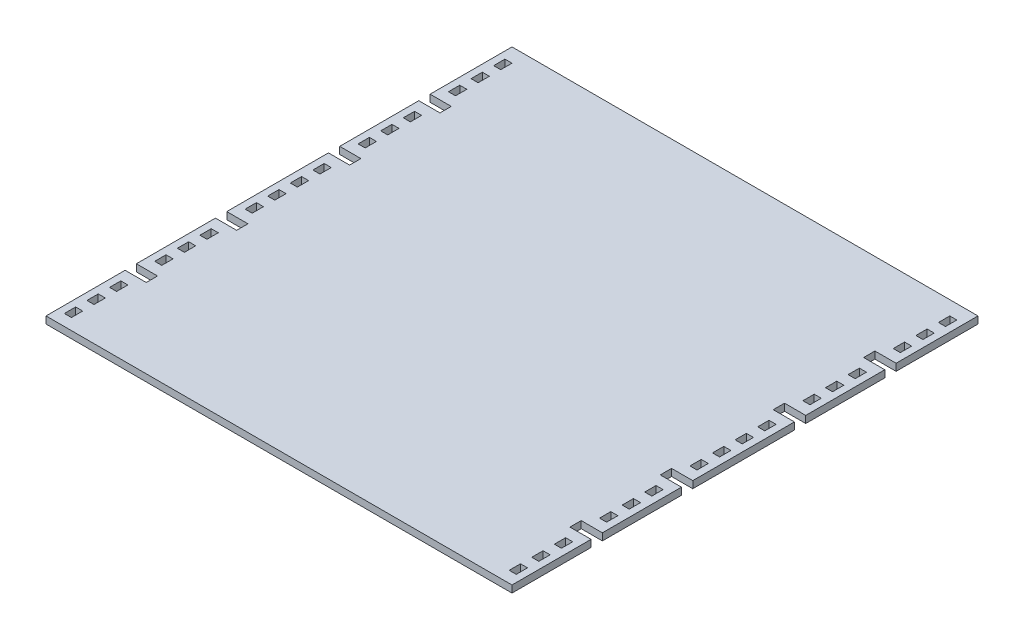
SolidWorks part; units mm, degrees
ref_plane "Front Plane" through (0, 0, 0) normal (0, 0, 1) x (1, 0, 0)
ref_plane "Top Plane" through (0, 0, 0) normal (0, 1, 0) x (1, 0, 0)
ref_plane "Right Plane" through (0, 0, 0) normal (1, 0, 0) x (0, 0, -1)
sketch "Sketch2" plane through (0, 0, 0) normal (0, 1, 0) x (1, 0, 0)
  line L0 (46.1343, -170.1642) -> (46.1343, 39.3858) construction
  line L1 (-58.6407, -170.1642) -> (150.9093, -170.1642)
  line L2 (-58.6407, -170.1642) -> (-58.6407, -134.6042)
  line L3 (-58.6407, 39.3858) -> (150.9093, 39.3858)
  line L4 (150.9093, -170.1642) -> (150.9093, -134.6042)
  line L5 (-55.4657, -165.0842) -> (-52.2907, -165.0842)
  line L6 (-55.4657, -165.0842) -> (-55.4657, -160.0042)
  line L7 (-55.4657, -160.0042) -> (-52.2907, -160.0042)
  line L8 (-52.2907, -165.0842) -> (-52.2907, -160.0042)
  line L9 (144.5593, -165.0842) -> (144.5593, -160.0042)
  line L10 (147.7343, -160.0042) -> (144.5593, -160.0042)
  line L11 (147.7343, -165.0842) -> (147.7343, -160.0042)
  line L12 (147.7343, -165.0842) -> (144.5593, -165.0842)
  line L13 (-55.4657, -154.9242) -> (-52.2907, -154.9242)
  line L14 (-55.4657, -154.9242) -> (-55.4657, -149.8442)
  line L15 (-55.4657, -149.8442) -> (-52.2907, -149.8442)
  line L16 (-52.2907, -154.9242) -> (-52.2907, -149.8442)
  line L17 (-55.4657, -144.7642) -> (-52.2907, -144.7642)
  line L18 (-55.4657, -144.7642) -> (-55.4657, -139.6842)
  line L19 (-55.4657, -139.6842) -> (-52.2907, -139.6842)
  line L20 (-52.2907, -144.7642) -> (-52.2907, -139.6842)
  line L21 (-58.6407, 2.5558) -> (-58.6407, 39.3858)
  line L22 (-58.6407, -38.0842) -> (-58.6407, -2.5242)
  line L23 (-58.6407, -88.8842) -> (-58.6407, -43.1642)
  line L24 (-58.6407, -129.5242) -> (-58.6407, -93.9642)
  line L25 (-55.4657, -124.4442) -> (-52.2907, -124.4442)
  line L26 (-55.4657, -124.4442) -> (-55.4657, -119.3642)
  line L27 (-55.4657, -119.3642) -> (-52.2907, -119.3642)
  line L28 (-52.2907, -124.4442) -> (-52.2907, -119.3642)
  line L29 (-55.4657, -114.2842) -> (-52.2907, -114.2842)
  line L30 (-55.4657, -114.2842) -> (-55.4657, -109.2042)
  line L31 (-55.4657, -109.2042) -> (-52.2907, -109.2042)
  line L32 (-52.2907, -114.2842) -> (-52.2907, -109.2042)
  line L33 (-55.4657, -104.1242) -> (-52.2907, -104.1242)
  line L34 (-55.4657, -104.1242) -> (-55.4657, -99.0442)
  line L35 (-55.4657, -99.0442) -> (-52.2907, -99.0442)
  line L36 (-52.2907, -104.1242) -> (-52.2907, -99.0442)
  line L37 (150.9093, -129.5242) -> (150.9093, -93.9642)
  line L38 (150.9093, -88.8842) -> (150.9093, -43.1642)
  line L39 (150.9093, -38.0842) -> (150.9093, -2.5242)
  line L40 (150.9093, 2.5558) -> (150.9093, 39.3858)
  line L41 (-55.4657, -83.8042) -> (-52.2907, -83.8042)
  line L42 (-55.4657, -83.8042) -> (-55.4657, -78.7242)
  line L43 (-55.4657, -78.7242) -> (-52.2907, -78.7242)
  line L44 (-52.2907, -83.8042) -> (-52.2907, -78.7242)
  line L45 (-55.4657, -73.6442) -> (-52.2907, -73.6442)
  line L46 (-55.4657, -73.6442) -> (-55.4657, -68.5642)
  line L47 (-55.4657, -68.5642) -> (-52.2907, -68.5642)
  line L48 (-52.2907, -73.6442) -> (-52.2907, -68.5642)
  line L49 (-55.4657, -63.4842) -> (-52.2907, -63.4842)
  line L50 (-55.4657, -63.4842) -> (-55.4657, -58.4042)
  line L51 (-55.4657, -58.4042) -> (-52.2907, -58.4042)
  line L52 (-52.2907, -63.4842) -> (-52.2907, -58.4042)
  line L53 (-55.4657, -53.3242) -> (-52.2907, -53.3242)
  line L54 (-55.4657, -53.3242) -> (-55.4657, -48.2442)
  line L55 (-55.4657, -48.2442) -> (-52.2907, -48.2442)
  line L56 (-52.2907, -53.3242) -> (-52.2907, -48.2442)
  line L61 (-55.4657, -33.0042) -> (-52.2907, -33.0042)
  line L62 (-55.4657, -33.0042) -> (-55.4657, -27.9242)
  line L63 (-55.4657, -27.9242) -> (-52.2907, -27.9242)
  line L64 (-52.2907, -33.0042) -> (-52.2907, -27.9242)
  line L65 (-55.4657, -22.8442) -> (-52.2907, -22.8442)
  line L66 (-55.4657, -22.8442) -> (-55.4657, -17.7642)
  line L67 (-55.4657, -17.7642) -> (-52.2907, -17.7642)
  line L68 (-52.2907, -22.8442) -> (-52.2907, -17.7642)
  line L69 (-55.4657, -12.6842) -> (-52.2907, -12.6842)
  line L70 (-55.4657, -12.6842) -> (-55.4657, -7.6042)
  line L71 (-55.4657, -7.6042) -> (-52.2907, -7.6042)
  line L72 (-52.2907, -12.6842) -> (-52.2907, -7.6042)
  line L77 (-55.4657, 7.6358) -> (-52.2907, 7.6358)
  line L78 (-55.4657, 7.6358) -> (-55.4657, 12.7158)
  line L79 (-55.4657, 12.7158) -> (-52.2907, 12.7158)
  line L80 (-52.2907, 7.6358) -> (-52.2907, 12.7158)
  line L81 (-55.4657, 17.7958) -> (-52.2907, 17.7958)
  line L82 (-55.4657, 17.7958) -> (-55.4657, 22.8758)
  line L83 (-55.4657, 22.8758) -> (-52.2907, 22.8758)
  line L84 (-52.2907, 17.7958) -> (-52.2907, 22.8758)
  line L85 (-55.4657, 27.9558) -> (-52.2907, 27.9558)
  line L86 (-55.4657, 27.9558) -> (-55.4657, 33.0358)
  line L87 (-55.4657, 33.0358) -> (-52.2907, 33.0358)
  line L88 (-52.2907, 27.9558) -> (-52.2907, 33.0358)
  line L89 (144.5593, 27.9558) -> (144.5593, 33.0358)
  line L90 (147.7343, 33.0358) -> (144.5593, 33.0358)
  line L91 (147.7343, 27.9558) -> (147.7343, 33.0358)
  line L92 (147.7343, 27.9558) -> (144.5593, 27.9558)
  line L93 (144.5593, 17.7958) -> (144.5593, 22.8758)
  line L94 (147.7343, 22.8758) -> (144.5593, 22.8758)
  line L95 (147.7343, 17.7958) -> (147.7343, 22.8758)
  line L96 (147.7343, 17.7958) -> (144.5593, 17.7958)
  line L97 (144.5593, 7.6358) -> (144.5593, 12.7158)
  line L98 (147.7343, 12.7158) -> (144.5593, 12.7158)
  line L99 (147.7343, 7.6358) -> (147.7343, 12.7158)
  line L100 (147.7343, 7.6358) -> (144.5593, 7.6358)
  line L105 (144.5593, -12.6842) -> (144.5593, -7.6042)
  line L106 (147.7343, -7.6042) -> (144.5593, -7.6042)
  line L107 (147.7343, -12.6842) -> (147.7343, -7.6042)
  line L108 (147.7343, -12.6842) -> (144.5593, -12.6842)
  line L109 (144.5593, -22.8442) -> (144.5593, -17.7642)
  line L110 (147.7343, -17.7642) -> (144.5593, -17.7642)
  line L111 (147.7343, -22.8442) -> (147.7343, -17.7642)
  line L112 (147.7343, -22.8442) -> (144.5593, -22.8442)
  line L113 (144.5593, -33.0042) -> (144.5593, -27.9242)
  line L114 (147.7343, -27.9242) -> (144.5593, -27.9242)
  line L115 (147.7343, -33.0042) -> (147.7343, -27.9242)
  line L116 (147.7343, -33.0042) -> (144.5593, -33.0042)
  line L121 (144.5593, -53.3242) -> (144.5593, -48.2442)
  line L122 (147.7343, -48.2442) -> (144.5593, -48.2442)
  line L123 (147.7343, -53.3242) -> (147.7343, -48.2442)
  line L124 (147.7343, -53.3242) -> (144.5593, -53.3242)
  line L125 (144.5593, -63.4842) -> (144.5593, -58.4042)
  line L126 (147.7343, -58.4042) -> (144.5593, -58.4042)
  line L127 (147.7343, -63.4842) -> (147.7343, -58.4042)
  line L128 (147.7343, -63.4842) -> (144.5593, -63.4842)
  line L129 (144.5593, -73.6442) -> (144.5593, -68.5642)
  line L130 (147.7343, -68.5642) -> (144.5593, -68.5642)
  line L131 (147.7343, -73.6442) -> (147.7343, -68.5642)
  line L132 (147.7343, -73.6442) -> (144.5593, -73.6442)
  line L133 (144.5593, -83.8042) -> (144.5593, -78.7242)
  line L134 (147.7343, -78.7242) -> (144.5593, -78.7242)
  line L135 (147.7343, -83.8042) -> (147.7343, -78.7242)
  line L136 (147.7343, -83.8042) -> (144.5593, -83.8042)
  line L141 (144.5593, -104.1242) -> (144.5593, -99.0442)
  line L142 (147.7343, -99.0442) -> (144.5593, -99.0442)
  line L143 (147.7343, -104.1242) -> (147.7343, -99.0442)
  line L144 (147.7343, -104.1242) -> (144.5593, -104.1242)
  line L145 (144.5593, -114.2842) -> (144.5593, -109.2042)
  line L146 (147.7343, -109.2042) -> (144.5593, -109.2042)
  line L147 (147.7343, -114.2842) -> (147.7343, -109.2042)
  line L148 (147.7343, -114.2842) -> (144.5593, -114.2842)
  line L149 (144.5593, -124.4442) -> (144.5593, -119.3642)
  line L150 (147.7343, -119.3642) -> (144.5593, -119.3642)
  line L151 (147.7343, -124.4442) -> (147.7343, -119.3642)
  line L152 (147.7343, -124.4442) -> (144.5593, -124.4442)
  line L157 (144.5593, -144.7642) -> (144.5593, -139.6842)
  line L158 (147.7343, -139.6842) -> (144.5593, -139.6842)
  line L159 (147.7343, -144.7642) -> (147.7343, -139.6842)
  line L160 (147.7343, -144.7642) -> (144.5593, -144.7642)
  line L161 (144.5593, -154.9242) -> (144.5593, -149.8442)
  line L162 (147.7343, -149.8442) -> (144.5593, -149.8442)
  line L163 (147.7343, -154.9242) -> (147.7343, -149.8442)
  line L164 (147.7343, -154.9242) -> (144.5593, -154.9242)
  line L166 (150.9093, -129.5242) -> (141.3843, -129.5242)
  line L168 (150.9093, -134.6042) -> (141.3843, -134.6042)
  line L169 (141.3843, -129.5242) -> (141.3843, -134.6042)
  line L170 (150.9093, -88.8842) -> (141.3843, -88.8842)
  line L172 (150.9093, -93.9642) -> (141.3843, -93.9642)
  line L173 (141.3843, -88.8842) -> (141.3843, -93.9642)
  line L174 (150.9093, 2.5558) -> (141.3843, 2.5558)
  line L176 (150.9093, -2.5242) -> (141.3843, -2.5242)
  line L177 (141.3843, 2.5558) -> (141.3843, -2.5242)
  line L178 (150.9093, -38.0842) -> (141.3843, -38.0842)
  line L180 (150.9093, -43.1642) -> (141.3843, -43.1642)
  line L181 (141.3843, -38.0842) -> (141.3843, -43.1642)
  line L182 (-58.6407, 2.5558) -> (-49.1157, 2.5558)
  line L184 (-58.6407, -2.5242) -> (-49.1157, -2.5242)
  line L185 (-49.1157, 2.5558) -> (-49.1157, -2.5242)
  line L186 (-58.6407, -38.0842) -> (-49.1157, -38.0842)
  line L188 (-58.6407, -43.1642) -> (-49.1157, -43.1642)
  line L189 (-49.1157, -38.0842) -> (-49.1157, -43.1642)
  line L190 (-58.6407, -129.5242) -> (-49.1157, -129.5242)
  line L192 (-58.6407, -134.6042) -> (-49.1157, -134.6042)
  line L193 (-49.1157, -129.5242) -> (-49.1157, -134.6042)
  line L194 (-58.6407, -88.8842) -> (-49.1157, -88.8842)
  line L196 (-58.6407, -93.9642) -> (-49.1157, -93.9642)
  line L197 (-49.1157, -88.8842) -> (-49.1157, -93.9642)
  line L198 (-55.4657, -134.6042) -> (-52.2907, -134.6042) [skipped]
  line L199 (-55.4657, -134.6042) -> (-55.4657, -129.5242) [skipped]
  line L200 (-55.4657, -129.5242) -> (-52.2907, -129.5242) [skipped]
  line L201 (-52.2907, -134.6042) -> (-52.2907, -129.5242) [skipped]
  line L202 (-55.4657, -93.9642) -> (-52.2907, -93.9642) [skipped]
  line L203 (-55.4657, -93.9642) -> (-55.4657, -88.8842) [skipped]
  line L204 (-55.4657, -88.8842) -> (-52.2907, -88.8842) [skipped]
  line L205 (-52.2907, -93.9642) -> (-52.2907, -88.8842) [skipped]
  line L206 (-55.4657, -43.1642) -> (-52.2907, -43.1642) [skipped]
  line L207 (-55.4657, -43.1642) -> (-55.4657, -38.0842) [skipped]
  line L208 (-55.4657, -38.0842) -> (-52.2907, -38.0842) [skipped]
  line L209 (-52.2907, -43.1642) -> (-52.2907, -38.0842) [skipped]
  line L210 (-55.4657, -2.5242) -> (-52.2907, -2.5242) [skipped]
  line L211 (-55.4657, -2.5242) -> (-55.4657, 2.5558) [skipped]
  line L212 (-55.4657, 2.5558) -> (-52.2907, 2.5558) [skipped]
  line L213 (-52.2907, -2.5242) -> (-52.2907, 2.5558) [skipped]
  dimension "D1" = 209.55
  dimension "D2" = 209.55
  dimension "D3" = 3.175
  dimension "D4" = 3.175
  dimension "D5" = 5.08
  dimension "D6" = 5.08
  dimension "D8" = 9.525
  dimension "D7" = 20
extrude "Boss-Extrude1" add sketch "Sketch2" along normal blind 3.175
sketch "Sketch3" plane through (0, 0, 0) normal (0, -1, 0) x (1, 0, 0)
